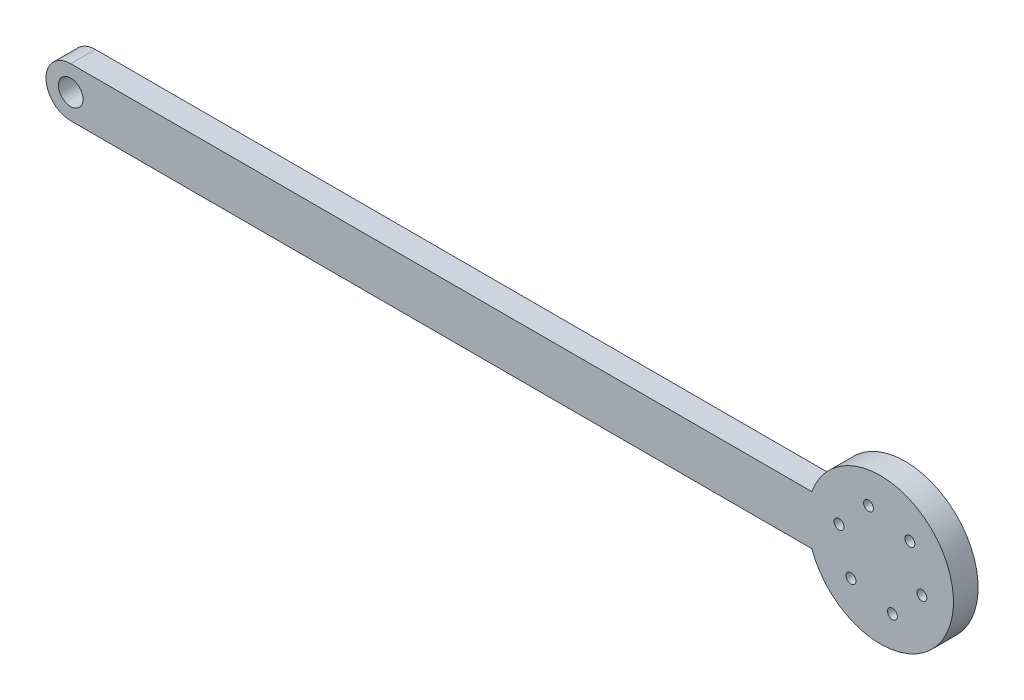
SolidWorks part; units mm, degrees
ref_plane "前视基准面" through (0, 0, 0) normal (0, 0, 1) x (1, 0, 0)
ref_plane "上视基准面" through (0, 0, 0) normal (0, 1, 0) x (1, 0, 0)
ref_plane "右视基准面" through (0, 0, 0) normal (1, 0, 0) x (0, 0, -1)
sketch "草图1" plane through (0, 0, 0) normal (0, 0, 1) x (1, 0, 0)
  line L1 (-73.6722, 28.1179) -> (226.3278, 28.1179)
  line L3 (-73.6722, 8.1179) -> (226.3278, 8.1179)
  arc A0 (-73.6722, 28.1179) -> (-73.6722, 8.1179) centre (-73.6722, 18.1179) ccw
  arc A2 (226.3278, 28.1179) -> (226.3278, 8.1179) centre (254.1328, 18.1179) cw
  circle A3 centre (-73.6722, 18.1179) radius 5
  circle A4 centre (249.288, 34.6736) radius 2
  circle A5 centre (266.048, 30.5915) radius 2
  circle A6 centre (270.8928, 14.0358) radius 2
  circle A7 centre (258.9776, 1.5622) radius 2
  circle A8 centre (242.2176, 5.6443) radius 2
  circle A9 centre (237.3727, 22.2) radius 2
  point P21 (254.1328, 18.1179)
  dimension "D1" = 17.25
  dimension "D2" = 6
extrude "凸台-拉伸1" add sketch "草图1" along normal blind 10
ref_plane "基准面1" through (-73.6722, 8.1179, 0) normal (1, 0, 0) x (0, 0, -1)
